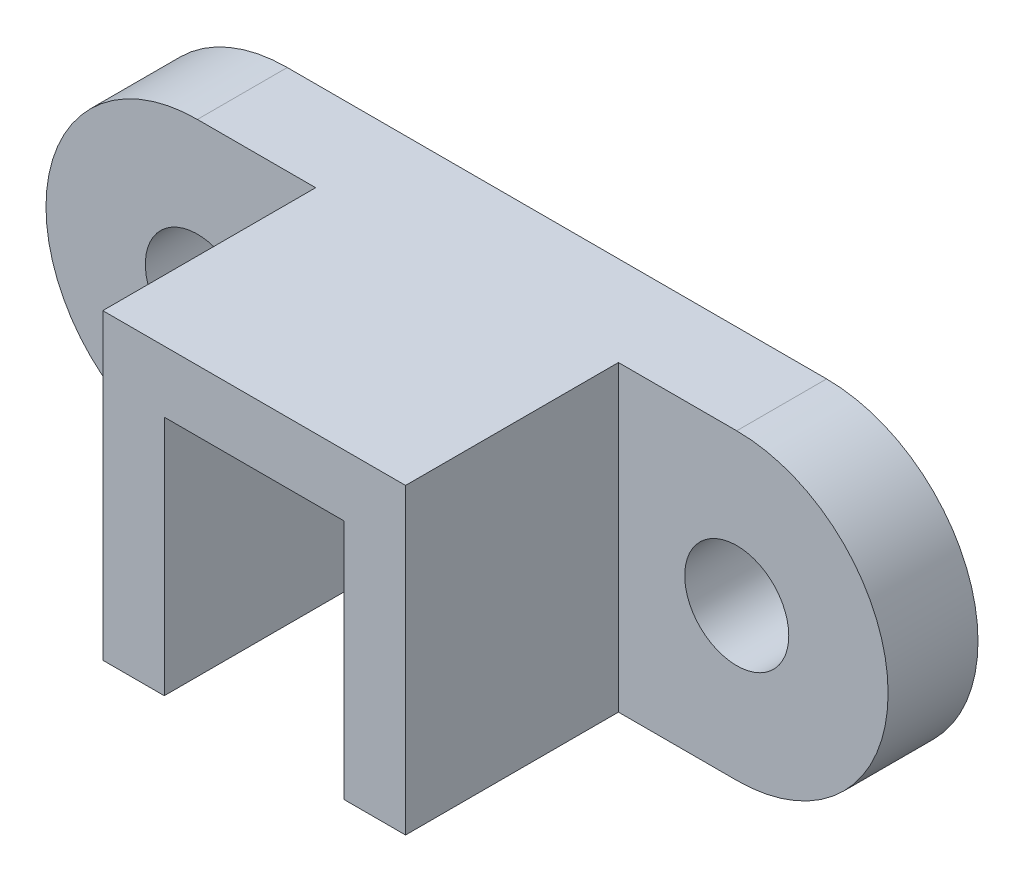
SolidWorks part; units mm, degrees
ref_plane "Front Plane" through (0, 0, 0) normal (0, 0, 1) x (1, 0, 0)
ref_plane "Top Plane" through (0, 0, 0) normal (0, 1, 0) x (1, 0, 0)
ref_plane "Right Plane" through (0, 0, 0) normal (1, 0, 0) x (0, 0, -1)
sketch "Sketch1" plane through (0, 0, 0) normal (0, 0, 1) x (1, 0, 0)
  line L0 (0, 0) -> (-114, 0) construction
  line L1 (0, -32) -> (-114, -32)
  line L2 (0, 32) -> (-114, 32)
  arc A0 (0, -32) -> (0, 32) centre (0, 0) ccw
  arc A1 (-114, 32) -> (-114, -32) centre (-114, 0) ccw
  circle A2 centre (-114, 0) radius 11
  circle A3 centre (0, 0) radius 11
  point P3 (-57, 0)
  dimension "D2" = 32
  dimension "D3" = 22
  dimension "D4" = 22
  dimension "D1" = 114
extrude "Boss-Extrude1" add sketch "Sketch1" along normal blind 19
sketch "Sketch3" plane through (0, 0, 19) normal (0, 0, 1) x (1, 0, 0)
  line L0 (-114, -32) -> (0, -32) construction
  line L1 (-89, 32) -> (-25, 32)
  line L2 (-89, 32) -> (-89, -32)
  line L3 (-89, -32) -> (-25, -32)
  line L4 (-25, 32) -> (-25, -32)
  line L5 (-89, 32) -> (-25, -32) construction
  line L6 (-89, -32) -> (-25, 32) construction
  circle A0 centre (-114, 0) radius 11 construction
  point P0 (-57, 0)
  dimension "D3" = 25
  dimension "D1" = 64
  dimension "D2" = 64
  dimension "D4" = 25
extrude "Boss-Extrude2" add sketch "Sketch3" along normal blind 45
sketch "Sketch7" plane through (-89, 0, 0) normal (-1, 0, 0) x (0, 0, 1)
  line L0 (64, -32) -> (64, 19)
  line L1 (64, 32) -> (64, -32) construction
  line L2 (64, 19) -> (13, -32)
  line L3 (19, -32) -> (0, -32) construction
  line L4 (13, -32) -> (64, -32)
  dimension "D1" = 13
  dimension "D2" = 13
extrude "Cut-Extrude1" cut sketch "Sketch7" against normal blind 38 from offset 13
